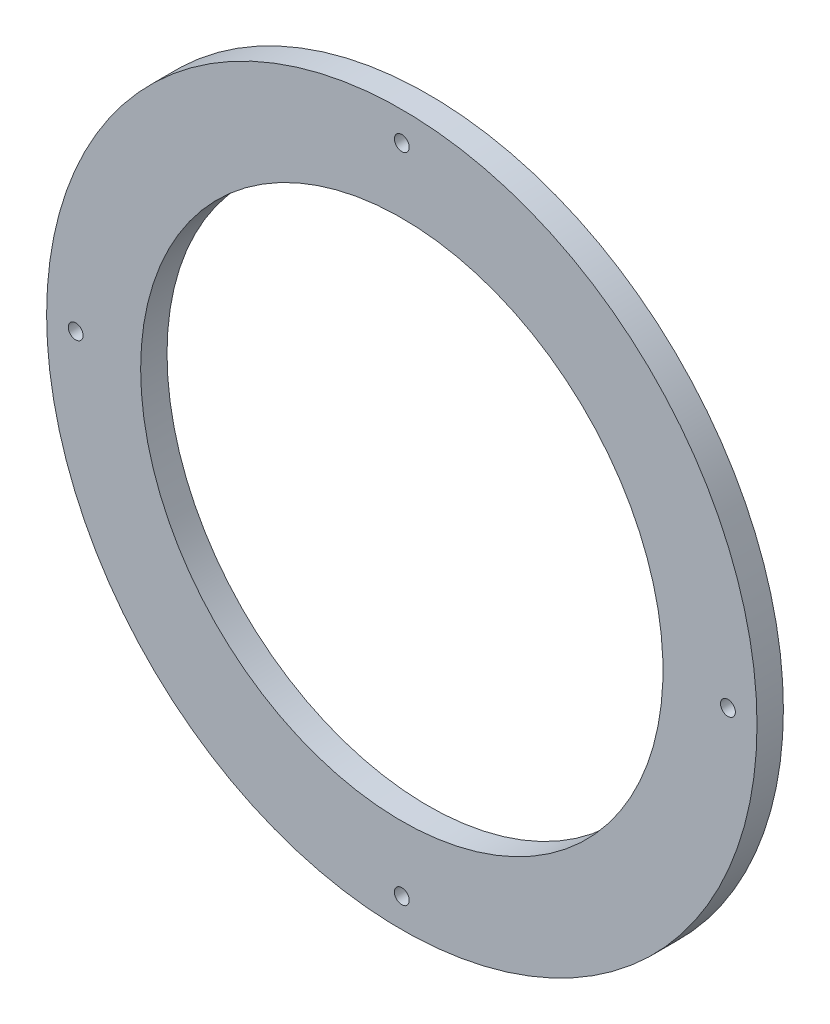
SolidWorks part; units mm, degrees
ref_plane "Front Plane" through (0, 0, 0) normal (0, 0, 1) x (1, 0, 0)
ref_plane "Top Plane" through (0, 0, 0) normal (0, 1, 0) x (1, 0, 0)
ref_plane "Right Plane" through (0, 0, 0) normal (1, 0, 0) x (0, 0, -1)
sketch "Sketch1" plane through (0, 0, 0) normal (0, 0, 1) x (1, 0, 0)
  line L0 (0, 78.5) -> (0, 0) construction
  line L7 (78.5, 0) -> (0, 0) construction
  circle A0 centre (0, 0) radius 85.5
  circle A1 centre (0, 78.5) radius 1.7859
  circle A2 centre (78.5, 0) radius 1.7859
  circle A3 centre (0, -78.5) radius 1.7859
  circle A4 centre (-78.5, 0) radius 1.7859
  point P18 (0, 0)
  dimension "D1" = 171
  dimension "D4" = 3.5719
  dimension "D7" = 78.5
  dimension "D5" = 78.5
  dimension "D6" = 4
extrude "Boss-Extrude1" add sketch "Sketch1" along normal blind 6.35
sketch "Sketch2" [suppressed] plane through (0, 0, 0) normal (0, 0, -1) x (-1, 0, 0)
  line L1 (34.925, 57.15) -> (-34.925, 57.15)
  line L2 (34.925, 57.15) -> (34.925, -57.15)
  line L3 (34.925, -57.15) -> (-34.925, -57.15)
  line L4 (-34.925, 57.15) -> (-34.925, -57.15)
  line L5 (34.925, 57.15) -> (-34.925, -57.15) construction
  line L6 (34.925, -57.15) -> (-34.925, 57.15) construction
  point P0 (0, 0)
  dimension "D1" = 69.85
  dimension "D2" = 114.3
extrude "Cut-Extrude1" [suppressed] cut sketch "Sketch2" against normal through all
sketch "Sketch4" [suppressed] plane through (0, 0, 0) normal (0, 0, 1) x (1, 0, 0)
  line L0 (-10.5753, 63.3127) -> (10.5753, 63.3127)
  line L1 (23.9337, 20.087) -> (5.5609, 6.2059)
  line L2 (0, -60.1313) -> (0, 63.3127) construction
  line L3 (-35.2806, 44.2107) -> (35.2806, 44.2107) construction
  line L4 (-34.9321, -41.8368) -> (-1.0296, -41.8368) construction
  line L5 (3.822, 0.3425) -> (4.8401, -0.9039)
  line L6 (4.8401, -0.9039) -> (6.2041, -2.103)
  line L7 (6.2041, -2.103) -> (9.1763, -4.1225)
  line L8 (5.5221, -63.3127) -> (-5.5221, -63.3127)
  line L9 (0, -63.3127) -> (0, 63.3127) construction
  line L10 (0, 63.3127) -> (0, -63.3127)
  line L11 (0, -85.5) -> (0, 85.5) construction
  line L12 (-85.4999, 0.1573) -> (85.4999, 0.1573) construction
  line L13 (-6.2041, -2.103) -> (-9.1763, -4.1225)
  line L14 (-4.8401, -0.9039) -> (-6.2041, -2.103)
  line L15 (-3.822, 0.3425) -> (-4.8401, -0.9039)
  line L16 (-23.9337, 20.087) -> (-5.5609, 6.2059)
  line L17 (3.2692, 2.4584) -> (-3.2692, 2.4584) construction
  arc A0 (10.5753, 63.3127) -> (25.7679, 58.999) centre (10.5753, 34.4019) cw
  arc A1 (25.7679, 58.999) -> (35.2806, 44.2107) centre (15.0545, 41.6538) cw
  arc A2 (35.2806, 44.2107) -> (34.1036, 36.011) centre (19.7808, 42.2513) cw
  arc A3 (34.1036, 36.011) -> (23.9337, 20.087) centre (-21.1263, 60.0741) cw
  arc A4 (5.5609, 6.2059) -> (3.2692, 2.4584) centre (9.1763, 1.4206) ccw
  arc A5 (3.2692, 2.4584) -> (3.822, 0.3425) centre (5.8559, 2.004) ccw
  arc A6 (9.1763, -4.1225) -> (18.5651, -11.0062) centre (-82.1114, -138.4749) cw
  arc A7 (18.5651, -11.0062) -> (31.7982, -26.1892) centre (-15.2929, -53.8745) cw
  arc A8 (31.7982, -26.1892) -> (34.6396, -36.6286) centre (14.0414, -36.6286) cw
  arc A9 (34.6396, -36.6286) -> (27.3698, -53.8745) centre (10.5487, -36.6286) cw
  arc A10 (27.3698, -53.8745) -> (20.287, -58.8608) centre (8.3322, -34.356) cw
  arc A11 (20.287, -58.8608) -> (5.5221, -63.3127) centre (-0.7981, -15.6409) cw
  circle A12 centre (0, 0) radius 85.5 construction
  arc A13 (-20.287, -58.8608) -> (-5.5221, -63.3127) centre (0.7981, -15.6409) ccw
  arc A14 (-27.3698, -53.8745) -> (-20.287, -58.8608) centre (-8.3322, -34.356) ccw
  arc A15 (-34.6396, -36.6286) -> (-27.3698, -53.8745) centre (-10.5487, -36.6286) ccw
  arc A16 (-31.7982, -26.1892) -> (-34.6396, -36.6286) centre (-14.0414, -36.6286) ccw
  arc A17 (-18.5651, -11.0062) -> (-31.7982, -26.1892) centre (15.2929, -53.8745) ccw
  arc A18 (-9.1763, -4.1225) -> (-18.5651, -11.0062) centre (82.1114, -138.4749) ccw
  arc A19 (-3.2692, 2.4584) -> (-3.822, 0.3425) centre (-5.8559, 2.004) cw
  arc A20 (-5.5609, 6.2059) -> (-3.2692, 2.4584) centre (-9.1763, 1.4206) cw
  arc A21 (-34.1036, 36.011) -> (-23.9337, 20.087) centre (21.1263, 60.0741) ccw
  arc A22 (-35.2806, 44.2107) -> (-34.1036, 36.011) centre (-19.7808, 42.2513) ccw
  arc A23 (-25.7679, 58.999) -> (-35.2806, 44.2107) centre (-15.0545, 41.6538) ccw
  arc A24 (-10.5753, 63.3127) -> (-25.7679, 58.999) centre (-10.5753, 34.4019) ccw
  point P44 (0, 0)
  dimension "D1" = 35.2806
  dimension "D2" = 123.444
  dimension "D3" = 2.3011
sketch "Sketch6" [suppressed] plane through (0, 0, 0) normal (0, 0, -1) x (-1, 0, 0)
  circle A0 centre (0, 0) radius 62.865
  dimension "D1" = 125.73
extrude "Cut-Extrude3" [suppressed] cut sketch "Sketch6" against normal through all
sketch "Sketch7" plane through (0, 0, 0) normal (0, 0, -1) x (-1, 0, 0)
  circle A0 centre (0, 0) radius 62.865
  dimension "D1" = 125.73
extrude "Cut-Extrude4" cut sketch "Sketch7" against normal through all
